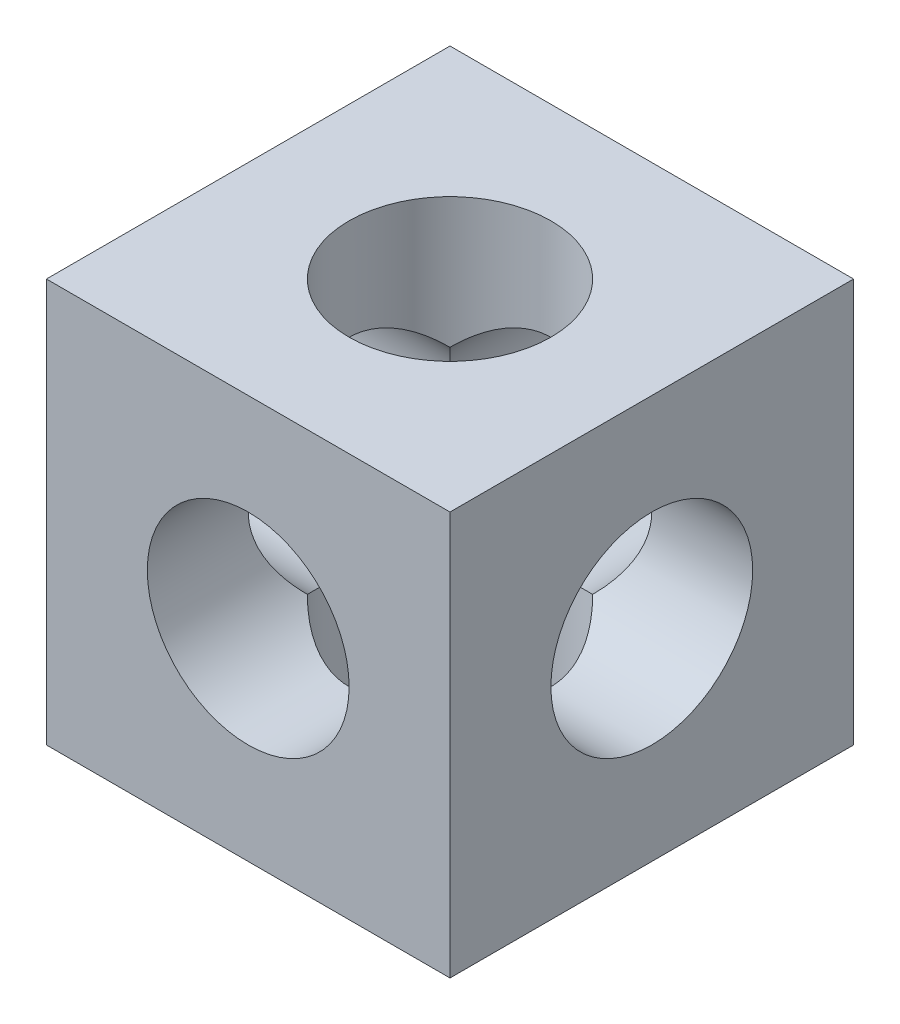
SolidWorks part; units mm, degrees
material "Pine"
ref_plane "Front" through (0, 0, 0) normal (0, 0, 1) x (1, 0, 0)
ref_plane "Top" through (0, 0, 0) normal (0, 1, 0) x (1, 0, 0)
ref_plane "Right" through (0, 0, 0) normal (1, 0, 0) x (0, 0, -1)
sketch "Sketch1" plane through (0, 0, 0) normal (0, 1, 0) x (1, 0, 0)
  line L1 (-25.4, 25.4) -> (25.4, 25.4)
  line L2 (-25.4, 25.4) -> (-25.4, -25.4)
  line L3 (-25.4, -25.4) -> (25.4, -25.4)
  line L4 (25.4, 25.4) -> (25.4, -25.4)
  line L5 (-25.4, 25.4) -> (25.4, -25.4) construction
  line L6 (-25.4, -25.4) -> (25.4, 25.4) construction
  point P0 (0, 0)
  dimension "D1" = 50.8
  dimension "D2" = 50.8
extrude "Boss-Extrude1" add sketch "Sketch1" along normal mid plane 50.8
sketch "Sketch2" plane through (0, 0, 25.4) normal (0, 0, 1) x (1, 0, 0)
  circle A0 centre (0, 0) radius 12.7
  dimension "D1" = 25.4
extrude "Cut-Extrude1" cut sketch "Sketch2" against normal through all
sketch "Sketch3" plane through (25.4, 0, 0) normal (1, 0, 0) x (0, 0, -1)
  circle A0 centre (0, 0) radius 12.7
  dimension "D1" = 25.4
extrude "Cut-Extrude2" cut sketch "Sketch3" against normal through all
sketch "Sketch4" plane through (0, 25.4, 0) normal (0, 1, 0) x (1, 0, 0)
  circle A0 centre (0, 0) radius 12.7
  dimension "D1" = 25.4
extrude "Cut-Extrude3" cut sketch "Sketch4" against normal through all
